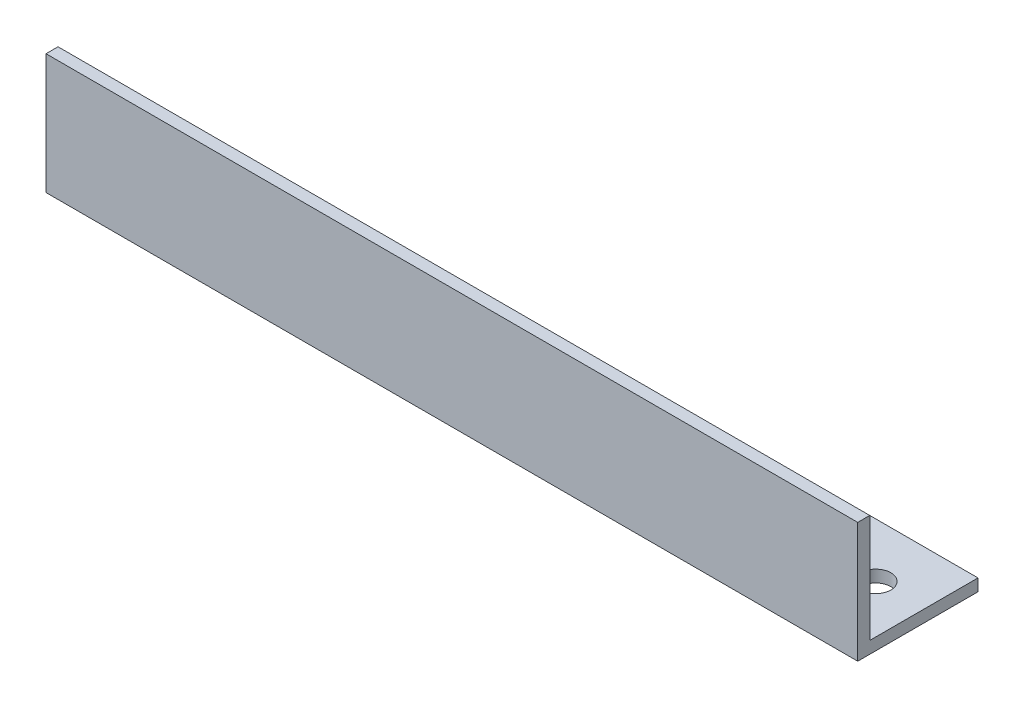
SolidWorks part; units mm, degrees
ref_plane "Front Plane" through (0, 0, 0) normal (0, 0, 1) x (1, 0, 0)
ref_plane "Top Plane" through (0, 0, 0) normal (0, 1, 0) x (1, 0, 0)
ref_plane "Right Plane" through (0, 0, 0) normal (1, 0, 0) x (0, 0, -1)
sketch "Sketch1" plane through (0, 0, 0) normal (1, 0, 0) x (0, 0, -1)
  line L0 (0, 20) -> (0, 0)
  line L1 (0, 0) -> (20, 0)
  line L2 (20, 0) -> (20, 2)
  line L3 (20, 2) -> (2, 2)
  line L4 (2, 2) -> (2, 20)
  line L5 (2, 20) -> (0, 20)
  dimension "D1" = 20
  dimension "D2" = 20
  dimension "D3" = 2
  dimension "D4" = 2
extrude "Boss-Extrude1" add sketch "Sketch1" against normal blind 135
sketch "Sketch3" plane through (0, 2, 0) normal (0, 1, 0) x (1, 0, 0)
  line L0 (-135, 11) -> (0, 11) construction
  line L1 (-135, 20) -> (-135, 2) construction
  line L2 (0, 20) -> (0, 2) construction
  circle A0 centre (-8, 11) radius 2.5
  circle A1 centre (-30, 11) radius 2.5
  dimension "D3" = 5
  dimension "D4" = 5
  dimension "D1" = 8
  dimension "D2" = 30
extrude "Cut-Extrude1" cut sketch "Sketch3" against normal blind 2
